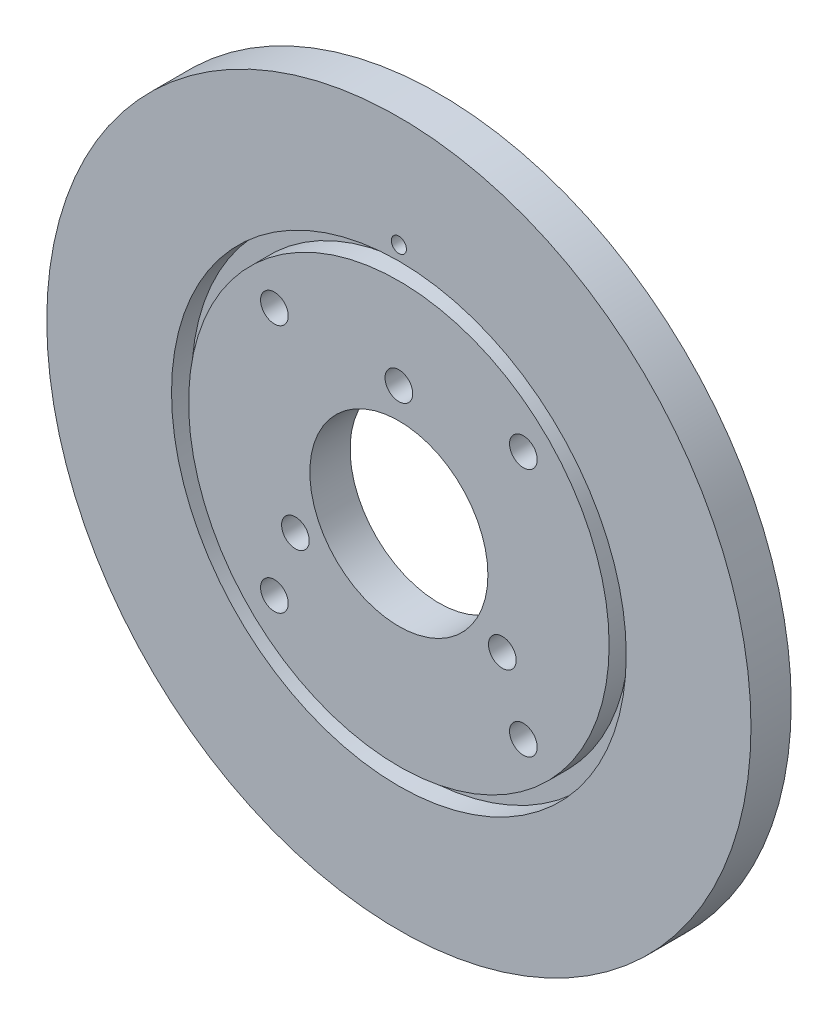
SolidWorks part; units mm, degrees
ref_plane "前视基准面" through (0, 0, 0) normal (0, 0, 1) x (1, 0, 0)
ref_plane "上视基准面" through (0, 0, 0) normal (0, 1, 0) x (1, 0, 0)
ref_plane "右视基准面" through (0, 0, 0) normal (1, 0, 0) x (0, 0, -1)
other "Configuration Table"
sketch "草图1" plane through (0, 0, 0) normal (0, 0, 1) x (1, 0, 0)
  circle A0 centre (0, 0) radius 70
  circle A1 centre (0, 0) radius 17.7
  circle A2 centre (24.7487, 24.7487) radius 2.75
  circle A3 centre (-24.7487, 24.7487) radius 2.75
  circle A4 centre (-24.7487, -24.7487) radius 2.75
  circle A5 centre (24.7487, -24.7487) radius 2.75
  circle A6 centre (0, 23.75) radius 2.75
  circle A7 centre (-20.5681, -11.875) radius 2.75
  circle A8 centre (20.5681, -11.875) radius 2.75
  circle A9 centre (0, 48) radius 1.5
extrude "凸台-拉伸1" add sketch "草图1" against normal blind 8
sketch "草图2" plane through (0, 0, 0) normal (0, 0, 1) x (1, 0, 0)
  circle A0 centre (0, 0) radius 45.2
  circle A1 centre (0, 0) radius 41.8
extrude "切除-拉伸2" cut sketch "草图2" against normal blind 4
